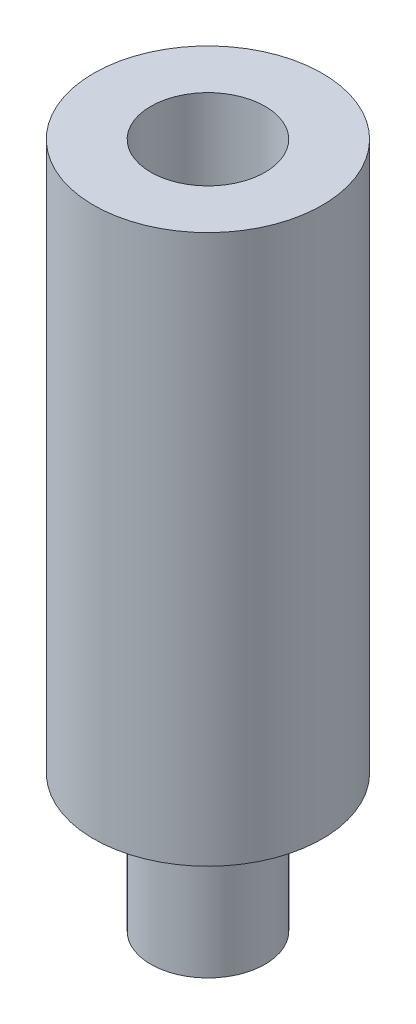
SolidWorks part; units mm, degrees
ref_plane "Front Plane" through (0, 0, 0) normal (0, 0, 1) x (1, 0, 0)
ref_plane "Top Plane" through (0, 0, 0) normal (0, 1, 0) x (1, 0, 0)
ref_plane "Right Plane" through (0, 0, 0) normal (1, 0, 0) x (0, 0, -1)
sketch "Sketch1" plane through (0, 0, 0) normal (0, 0, 1) x (1, 0, 0)
  line L0 (0, 0) -> (3.175, 0) construction
  line L1 (3.175, 0) -> (3.175, -15.24)
  line L2 (3.175, 0) -> (1.5875, 0)
  line L3 (3.175, -15.24) -> (1.5875, -15.24)
  line L5 (1.5875, -19.05) -> (0, -19.05)
  line L8 (1.5875, 0) -> (1.5875, -3.81)
  line L9 (1.5875, -3.81) -> (0, -3.81)
  line L11 (1.5875, -15.24) -> (1.5875, -19.05)
  line L12 (0, -3.81) -> (0, -19.05)
  dimension "D1" = 3.175
  dimension "D2" = 15.24
  dimension "D3" = 3.81
  dimension "D4" = 3.81
  dimension "D5" = 1.5875
revolve "Revolve2" add sketch "Sketch1" angle 360 about L12
